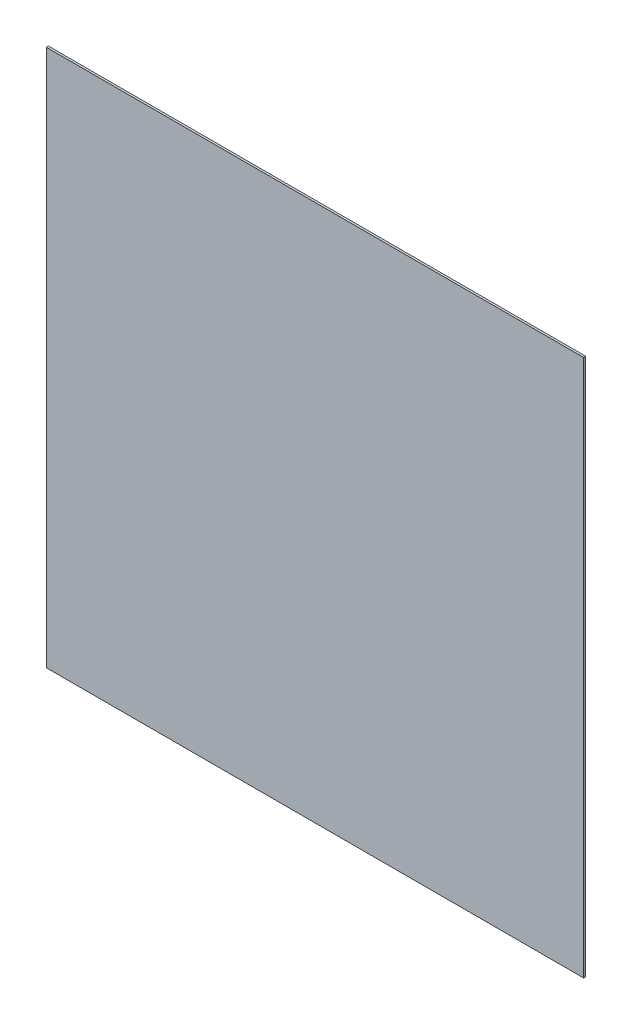
SolidWorks part; units mm, degrees
ref_plane "前基準面" through (0, 0, 0) normal (0, 0, 1) x (1, 0, 0)
ref_plane "上基準面" through (0, 0, 0) normal (0, 1, 0) x (1, 0, 0)
ref_plane "右基準面" through (0, 0, 0) normal (1, 0, 0) x (0, 0, -1)
sketch "草圖1" plane through (0, 0, 0) normal (0, 0, 1) x (1, 0, 0)
  line L0 (25.4, 25.4) -> (125.4, 25.4)
  line L1 (125.4, 25.4) -> (125.4, 125.4)
  line L2 (125.4, 125.4) -> (25.4, 125.4)
  line L3 (25.4, 125.4) -> (25.4, 25.4)
extrude "Board" add sketch "草圖1" along normal blind 0.3912
